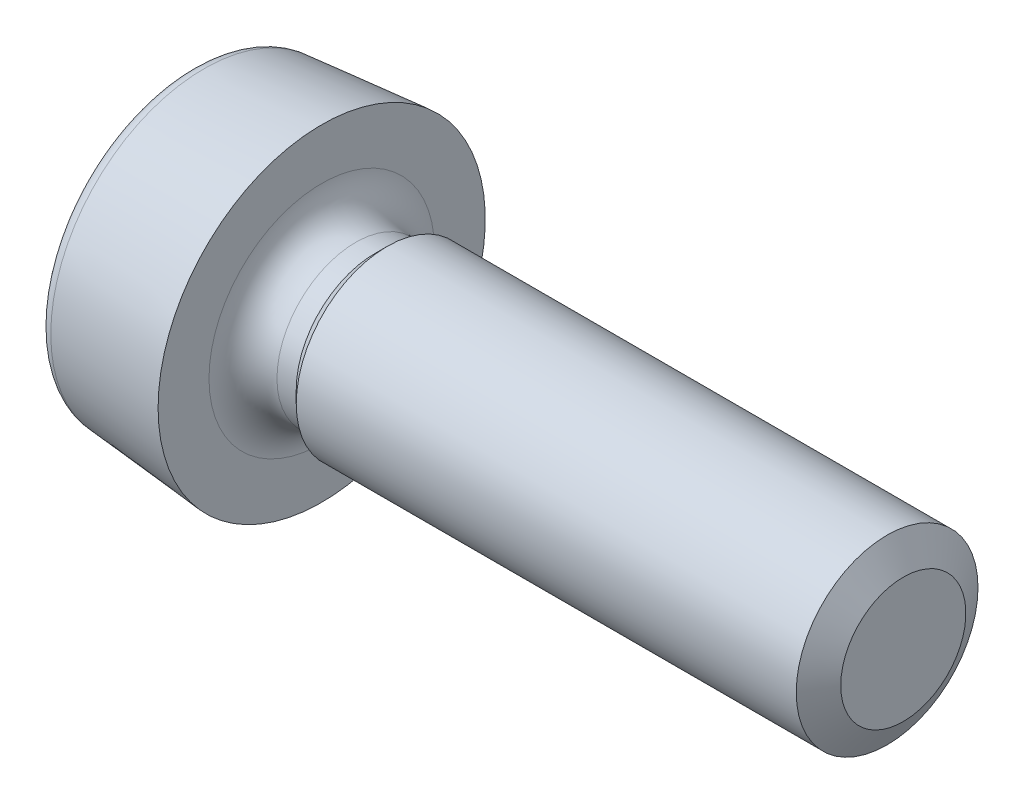
SolidWorks part; units mm, degrees
revolve "基体-旋转" add sketch "草图3" angle 360 about L0
sketch "草图3" plane through (0, 0, 0) normal (0, 0, 1) x (1, 0, 0)
  line L0 (-2.1696, 0) -> (16.014, 0) construction
  line L1 (0, 0) -> (9.8, 0)
  line L2 (9.8, 0) -> (9.8, 1.25)
  line L3 (9.8, 1.25) -> (2.7, 1.25)
  line L4 (2.7, 1.25) -> (2.5325, 1.0825)
  line L5 (2.5325, 1.0825) -> (2.2675, 1.0825)
  line L7 (1.8, 2.25) -> (0.1826, 2.1085)
  line L8 (0, 1.9093) -> (0, 0)
  line L9 (1.8, 1.55) -> (1.8, 2.25)
  arc A0 (1.8, 1.55) -> (2.2675, 1.0825) centre (2.2675, 1.55) ccw
  arc A1 (0.1826, 2.1085) -> (0, 1.9093) centre (0.2, 1.9093) ccw
  dimension "D4" = 0.2
  dimension "D1" = 5
  dimension "dk" = 4.5
  dimension "d" = 2.5
  dimension "D2" = 45
  dimension "da" = 3.1
  dimension "k" = 1.8
  dimension "D3" = 2.165
  dimension "a" = 0.9
  dimension "l" = 8
cosmetic thread "装饰螺纹线1" parameters "D2"=2.165
material "AISI 304"
ref_plane "前视" through (0, 0, 0) normal (0, 0, 1) x (1, 0, 0)
ref_plane "上视" through (0, 0, 0) normal (0, 1, 0) x (1, 0, 0)
ref_plane "右视" through (0, 0, 0) normal (1, 0, 0) x (0, 0, -1)
sketch "尺寸草图" plane through (0, 0, 0) normal (0, 0, 1) x (1, 0, 0)
  line L0 (0, 0) -> (8, 0)
  line L1 (0, 0) -> (0, 4.5)
  line L2 (8, 0) -> (8, 2.5)
  point P5 (0, 3.1)
  point P6 (1.8, 0)
  point P7 (2.7, 0)
  point P8 (7.55, 0)
  point P9 (6.8, 0)
  point P10 (5.3, 0)
  point P11 (0, 0.1)
  dimension "dk" = 4.5
  dimension "d" = 2.5
  dimension "da" = 3.1
  dimension "k" = 1.8
  dimension "a" = 0.9
  dimension "l" = 8
  dimension "P" = 0.45
  dimension "h" = 1.2
  dimension "m" = 2.7
  dimension "r" = 0.1
sketch "草图4" plane through (0, 0, 0) normal (0, 0, 1) x (1, 0, 0)
  line L0 (9.5774, 1.25) -> (10.0274, 1.25)
  line L1 (10.0274, 1.25) -> (9.8, 0.8603)
  line L2 (9.8, 0.8603) -> (9.5774, 1.25)
  line L3 (9.8, 1.25) -> (2.7, 1.25) construction
  line L4 (9.8, -1.25) -> (9.8, 1.25) construction
  line L5 (-0.218, 0) -> (14.7427, 0) construction
  line L6 (-2.1696, 0) -> (16.014, 0) construction
  dimension "D1" = 0.45
  dimension "D2" = 0.3897
  dimension "D3" = 60
revolve "切除-旋转1" cut sketch "草图4" angle 360 about L5
pattern_linear "阵列(线性)1" [suppressed] count 16 spacing 0.45 along (1, 0, 0)
sketch "草图5" plane through (0, 0, 0) normal (-1, 0, 0) x (0, 0, 1)
  line L1 (-0.225, 1.35) -> (0.225, 1.35)
  line L2 (-0.225, 1.35) -> (-0.225, -1.35)
  line L3 (-0.225, -1.35) -> (0.225, -1.35)
  line L4 (0.225, 1.35) -> (0.225, -1.35)
  point P4 (-0.225, 0)
  point P5 (0, 1.35)
  dimension "m" = 2.7
  dimension "D1" = 0.45
ref_plane "基准面1" through (1.2, 0, 0) normal (1, 0, 0) x (0, 0, -1)
sketch "草图6" plane through (1.2, 0, 0) normal (1, 0, 0) x (0, 0, -1)
  point P0 (0, 0)
loft "切除-放样1" cut profiles "草图5", "草图6"
pattern_circular "阵列(圆周)1" count 2 every 90 about axis through (0, 0, 0) along (1, 0, 0) of "切除-放样1"
equation "\"l@草图3\" = \"l@尺寸草图\""
equation "\"dk@草图3\" = \"dk@尺寸草图\""
equation "\"da@草图3\" = \"da@尺寸草图\""
equation "\"D4@草图3\" = \"r@尺寸草图\"*2"
equation "\"k@草图3\" = \"k@尺寸草图\""
equation "\"a@草图3\" = \"a@尺寸草图\""
equation "\"D3@草图3\" = \"d@尺寸草图\"*0.866"
equation "\"d@草图3\" = \"d@尺寸草图\""
equation "\"D2@装饰螺纹线1\" = \"d@尺寸草图\"*0.866"
equation "\"D1@草图4\" = \"P@尺寸草图\""
equation "\"D2@草图4\" = \"P@尺寸草图\"*0.866"
equation "\"D3@阵列(线性)1\" = \"P@尺寸草图\""
equation "\"D1@阵列(线性)1\" = (\"l@尺寸草图\"-\"a@尺寸草图\")/\"P@尺寸草图\""
equation "\"D1@基准面1\" = \"h@尺寸草图\""
equation "\"m@草图5\" = \"m@尺寸草图\""
equation "\"D1@草图5\" = \"P@尺寸草图\""
